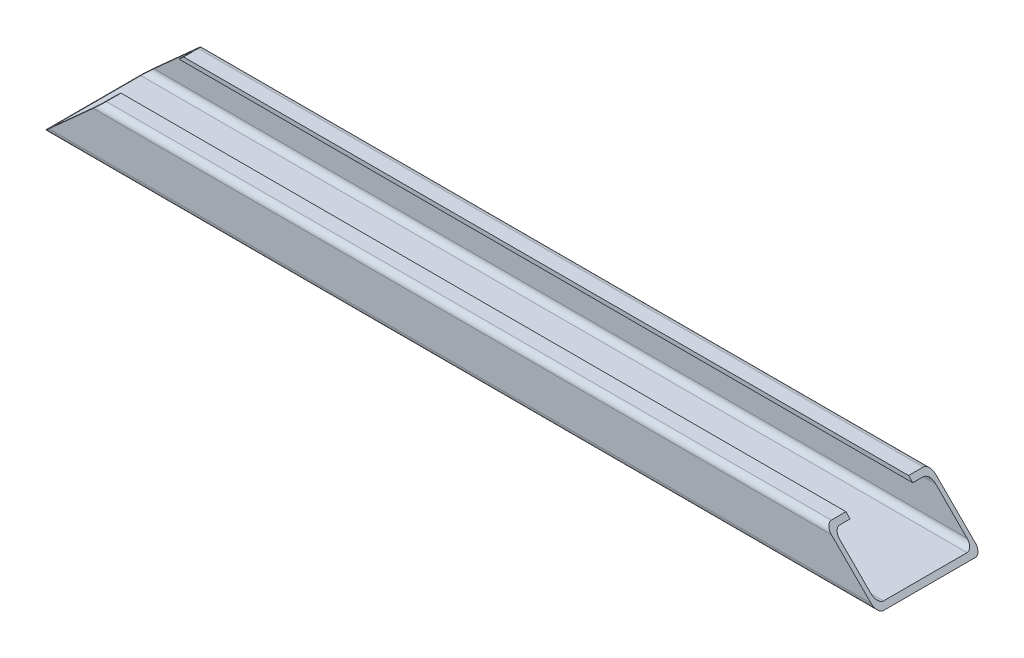
SolidWorks part; units mm, degrees
material "AISI 1045 Aço, trefilado"
ref_plane "Plano frontal" through (0, 0, 0) normal (0, 0, 1) x (1, 0, 0)
ref_plane "Plano superior" through (0, 0, 0) normal (0, 1, 0) x (1, 0, 0)
ref_plane "Plano direito" through (0, 0, 0) normal (1, 0, 0) x (0, 0, -1)
sketch "Esboço1" plane through (0, 0, 0) normal (1, 0, 0) x (0, 0, -1)
  line L0 (-46, 21) -> (-46, -21)
  line L1 (-50, 25) -> (-30, 25)
  line L2 (-50, 25) -> (-50, -25)
  line L3 (-50, -25) -> (50, -25)
  line L4 (50, 25) -> (50, -25)
  line L5 (-50, 25) -> (50, -25) construction
  line L6 (-50, -25) -> (50, 25) construction
  line L7 (-46, -21) -> (46, -21)
  line L8 (46, 21) -> (46, -21)
  line L9 (-46, 21) -> (-30, 21)
  line L10 (-30, 25) -> (-30, 21)
  line L13 (30, 25) -> (30, 21)
  line L14 (30, 21) -> (46, 21)
  line L15 (-46, 21) -> (46, 21) construction
  line L16 (30, 25) -> (50, 25)
  line L17 (-50, 25) -> (50, 25) construction
  point P0 (0, 0)
  dimension "D1" = 100
  dimension "D2" = 50
  dimension "D4" = 20
  dimension "D5" = 20
  dimension "D3" = 4
extrude "Ressalto-extrusão1" add sketch "Esboço1" along normal blind 800
fillet "Filete1" radius 6 8 edges at (400, 21, -46) (400, 21, 46) (400, 25, 50) (400, 25, -50) (400, -25, -50) (400, -21, -46) (400, -21, 46) (400, -25, 50)
sketch "Esboço3" plane through (0, 0, 0) normal (0, 0, 1) x (1, 0, 0)
  line L0 (0, -25) -> (184.7676, 159.7676)
  line L1 (184.7676, 159.7676) -> (-208.6154, 104.9391)
  line L2 (-208.6154, 104.9391) -> (0, -25)
  line L3 (0, 19) -> (0, -19) construction
  line L4 (800, -25) -> (613.271, 161.729)
  line L5 (613.271, 161.729) -> (1063.829, 161.729)
  line L6 (1063.829, 161.729) -> (800, -25)
  line L7 (800, -25) -> (0, -25) construction
  dimension "D1" = 45
  dimension "D2" = 45
extrude "Corte-extrusão1" cut sketch "Esboço3" against normal mid plane 100
sketch "Esboço4" plane through (0, 0, 0) normal (0, 0, 1) x (1, 0, 0)
  line L0 (0, -25) -> (86.0275, 52.4595)
  line L1 (86.0275, 52.4595) -> (-33.3448, 67.5814)
  line L2 (-33.3448, 67.5814) -> (0, -25)
  line L3 (6, -19) -> (44, 19) construction
  dimension "D1" = 3
extrude "Corte-extrusão2" cut sketch "Esboço4" against normal mid plane 100
